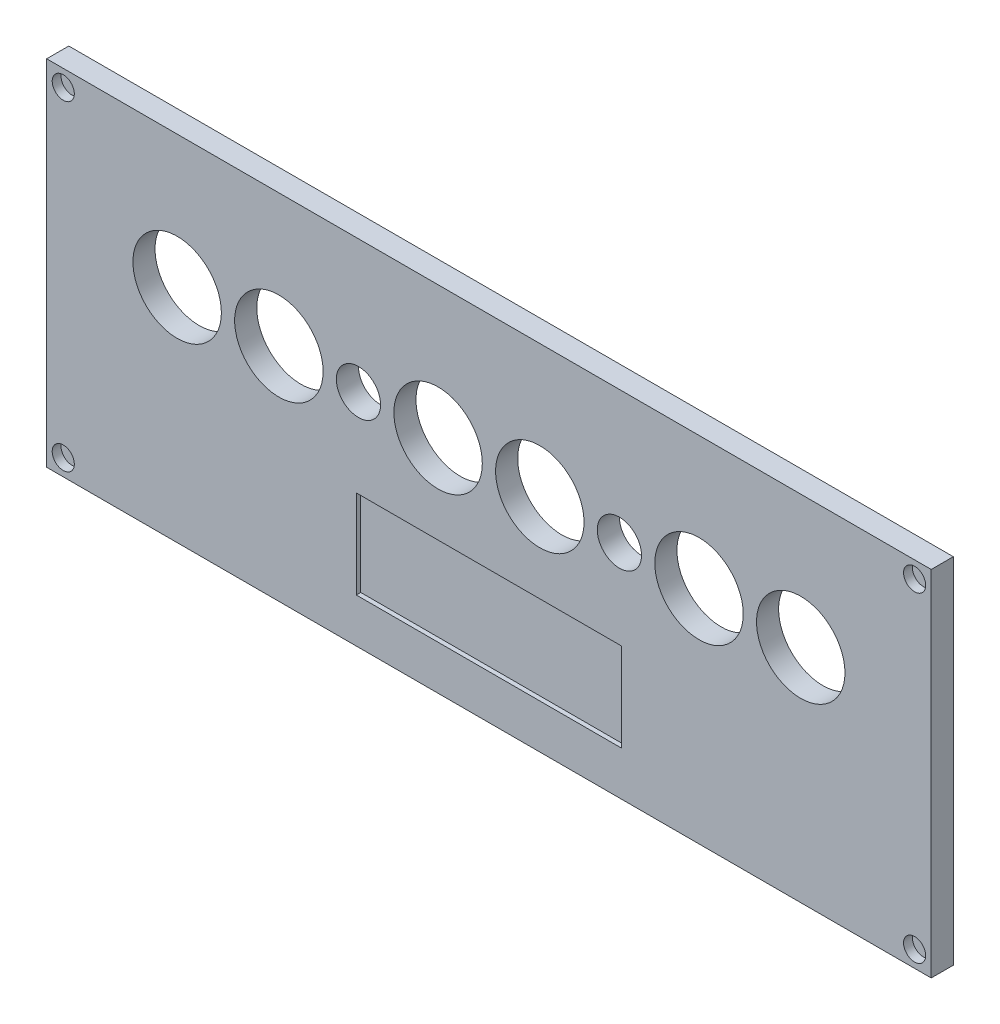
SolidWorks part; units mm, degrees
ref_plane "Alzado" through (0, 0, 0) normal (0, 0, 1) x (1, 0, 0)
ref_plane "Planta" through (0, 0, 0) normal (0, 1, 0) x (1, 0, 0)
ref_plane "Vista lateral" through (0, 0, 0) normal (1, 0, 0) x (0, 0, -1)
sketch "Croquis1" plane through (0, 0, 0) normal (0, 0, 1) x (1, 0, 0)
  line L1 (-100, -40) -> (100, -40)
  line L2 (-100, -40) -> (-100, 40)
  line L3 (-100, 40) -> (100, 40)
  line L4 (100, -40) -> (100, 40)
  line L5 (-100, -40) -> (100, 40) construction
  line L6 (-100, 40) -> (100, -40) construction
  point P0 (0, 0)
  dimension "D1" = 200
  dimension "D2" = 80
extrude "Saliente-Extruir1" add sketch "Croquis1" along normal blind 5
sketch "Croquis2" plane through (0, 0, 5) normal (0, 0, 1) x (1, 0, 0)
  line L0 (-100, 40) -> (-100, -40) construction
  line L1 (100, 40) -> (-100, 40) construction
  circle A0 centre (-96.25, 36.25) radius 2.5
  circle A1 centre (96.25, 36.25) radius 2.5
  circle A2 centre (96.25, -36.25) radius 2.5
  circle A3 centre (-96.25, -36.25) radius 2.5
  dimension "D1" = 5
  dimension "D2" = 3.75
  dimension "D3" = 3.75
  dimension "D4" = 2
  dimension "D5" = 2
extrude "Cortar-Extruir1" cut sketch "Croquis2" against normal blind 2 contours A0 | A3 | A2 | A1
sketch "Croquis3" plane through (0, 0, 5) normal (0, 0, 1) x (1, 0, 0)
  line L0 (0, 0) -> (0, -40) construction
  line L1 (-100, -40) -> (100, -40) construction
  line L3 (-30, -30) -> (30, -30)
  line L4 (-30, -30) -> (-30, -10)
  line L5 (-30, -10) -> (30, -10)
  line L6 (30, -30) -> (30, -10)
  line L7 (-30, -30) -> (30, -10) construction
  line L8 (-30, -10) -> (30, -30) construction
  point P5 (0, -20)
  dimension "D1" = 60
  dimension "D2" = 20
extrude "Cortar-Extruir2" cut sketch "Croquis3" against normal blind 1
sketch "Croquis4" plane through (0, 0, 5) normal (0, 0, 1) x (1, 0, 0)
  line L0 (-100, 0) -> (100, 0) construction
  line L1 (-100, 40) -> (-100, -40) construction
  line L2 (100, -40) -> (100, 40) construction
  line L3 (-100, 10) -> (100, 10) construction
  circle A0 centre (-70.5, 10) radius 10
  circle A1 centre (-47.5, 10) radius 10
  circle A2 centre (-29.5, 10) radius 5
  circle A3 centre (-11.5, 10) radius 10
  circle A4 centre (11.5, 10) radius 10
  circle A5 centre (29.5, 10) radius 5
  circle A6 centre (47.5, 10) radius 10
  circle A7 centre (70.5, 10) radius 10
  dimension "D2" = 20
  dimension "D3" = 20
  dimension "D4" = 10
  dimension "D5" = 20
  dimension "D6" = 20
  dimension "D7" = 10
  dimension "D8" = 20
  dimension "D9" = 20
  dimension "D1" = 10
  dimension "D10" = 29.5
  dimension "D11" = 23
  dimension "D12" = 18
  dimension "D13" = 18
  dimension "D14" = 23
  dimension "D15" = 18
  dimension "D16" = 18
  dimension "D17" = 23
extrude "Cortar-Extruir3" cut sketch "Croquis4" against normal blind 5
